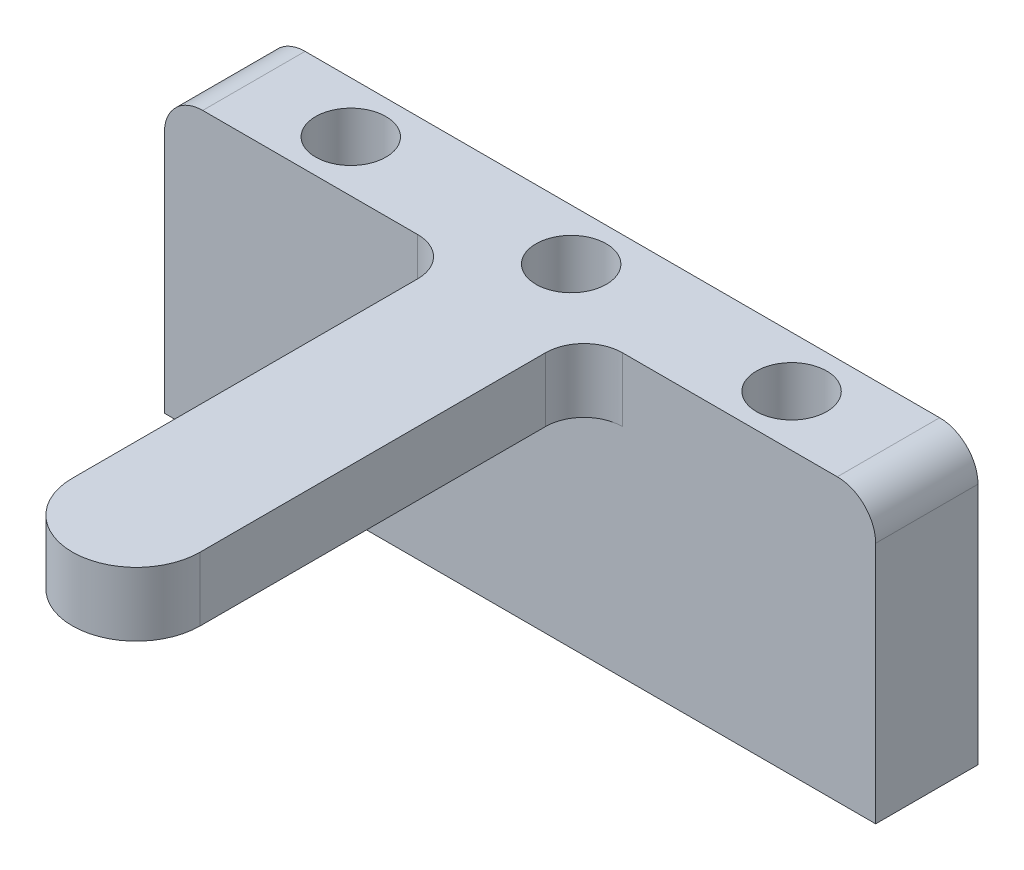
SolidWorks part; units mm, degrees
ref_plane "Front Plane" through (0, 0, 0) normal (0, 0, 1) x (1, 0, 0)
ref_plane "Top Plane" through (0, 0, 0) normal (0, 1, 0) x (1, 0, 0)
ref_plane "Right Plane" through (0, 0, 0) normal (1, 0, 0) x (0, 0, -1)
sketch "Sketch1" plane through (0, 0, 0) normal (0, 1, 0) x (1, 0, 0)
  line L1 (0, 0) -> (55.61, 0)
  line L2 (0, 0) -> (0, 8)
  line L3 (0, 8) -> (55.61, 8)
  line L4 (55.61, 0) -> (55.61, 8)
  circle A0 centre (27.805, 4) radius 2.75
  circle A1 centre (10.575, 4) radius 2.75
  circle A2 centre (45.035, 4) radius 2.75
  dimension "D3" = 17.23
  dimension "D1" = 55.61
  dimension "D2" = 8
  dimension "D4" = 17.23
  dimension "D5" = 27.805
extrude "Boss-Extrude1" add sketch "Sketch1" along normal blind 22
sketch "Sketch2" plane through (0, 0, 0) normal (0, 0, 1) x (1, 0, 0)
  line L0 (0, 22) -> (55.61, 22) construction
  line L1 (27.805, 22) -> (32.805, 22)
  line L2 (27.805, 22) -> (27.805, 17)
  line L3 (27.805, 17) -> (32.805, 17)
  line L4 (32.805, 22) -> (32.805, 17)
  line L6 (27.805, 22) -> (22.805, 22)
  line L7 (27.805, 22) -> (27.805, 17)
  line L8 (27.805, 17) -> (22.805, 17)
  line L9 (22.805, 22) -> (22.805, 17)
  line M6 (55.61, 22) -> (0, 22)
  dimension "D1" = 5
  dimension "D2" = 5
  dimension "D3" = 5
extrude "Boss-Extrude2" add sketch "Sketch2" along normal blind 30 contours L9 L8 L2 M6 | L4 L2 L3 M6
sketch "Sketch3" plane through (0, 22, 0) normal (0, 1, 0) x (1, 0, 0)
  line L0 (32.805, -30) -> (22.805, -30) construction
  line L1 (22.805, -30) -> (32.805, -30)
  arc A0 (32.805, -30) -> (22.805, -30) centre (27.805, -30) cw
extrude "Boss-Extrude3" add sketch "Sketch3" against normal blind 5
fillet "Fillet1" radius 3 4 edges at (55.61, 22, -4) (0, 22, -4) (32.805, 19.5, 0) (22.805, 19.5, 0)
